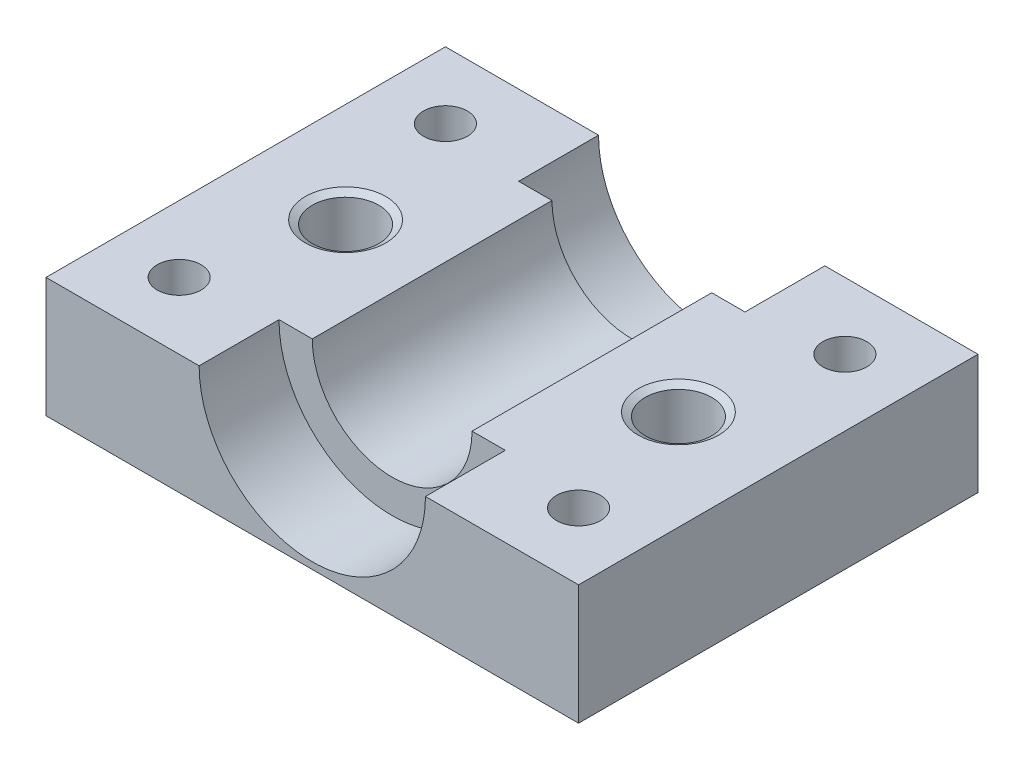
SolidWorks part; units mm, degrees
material "Д16Т ГОСТ 4784-74"
ref_plane "Спереди" through (0, 0, 0) normal (0, 0, 1) x (1, 0, 0)
ref_plane "Сверху" through (0, 0, 0) normal (0, 1, 0) x (1, 0, 0)
ref_plane "Справа" through (0, 0, 0) normal (1, 0, 0) x (0, 0, -1)
sketch "Эскиз1" plane through (0, 0, 0) normal (0, 0, 1) x (1, 0, 0)
  line L0 (28.5, 9) -> (40, 9)
  line L1 (0, 0) -> (40, 0)
  line L2 (0, 0) -> (0, 9)
  line L3 (0, 9) -> (11.5, 9)
  line L4 (40, 0) -> (40, 9)
  line L5 (11.5, 9) -> (28.5, 9) construction
  arc A0 (11.5, 9) -> (28.5, 9) centre (20, 9) ccw
  dimension "D1" = 17
  dimension "D2" = 9
  dimension "D3" = 40
extrude "Бобышка-Вытянуть1" add sketch "Эскиз1" along normal blind 24 and the other way blind 6
sketch "Эскиз3" plane through (0, 0, 0) normal (0, 0, 1) x (1, 0, 0)
  line L0 (11.5, 9) -> (14, 9)
  line L1 (26, 9) -> (28.5, 9)
  arc A0 (14, 9) -> (26, 9) centre (20, 9) ccw
  arc A1 (11.5, 9) -> (28.5, 9) centre (20, 9) ccw
  arc A2 (11.5, 9) -> (28.5, 9) centre (20, 9) ccw construction
  dimension "D1" = 12
extrude "Бобышка-Вытянуть2" add sketch "Эскиз3" along normal blind 18
hole_wizard "Отверстие обработанное метчиком M41" positions "Эскиз5" profile "Эскиз4" tap size "M4" standard "DIN"
sketch "Эскиз5" plane through (0, 0, 0) normal (0, -1, 0) x (1, 0, 0)
  line L0 (20, 24) -> (20, -6) construction
  line L1 (0, 24) -> (40, 24) construction
  line L2 (0, -6) -> (40, -6) construction
  line L4 (20, 9) -> (40, 9) construction
  line L5 (40, -6) -> (40, 24) construction
  point P0 (35, 19)
  point P18 (35, -1)
  point P19 (5, 19)
  point P20 (5, -1)
  dimension "D1" = 15
  dimension "D2" = 10
sketch "Эскиз4" plane through (35, 0, 19) normal (1, 0, 0) x (0, 0, -1)
  line L0 (0, 0) -> (0, 12.4914)
  line L1 (0, 12.4914) -> (1.65, 11.5)
  line L2 (1.65, 11.5) -> (1.65, 0.2165)
  line L3 (1.65, 0.2165) -> (2.025, 0)
  line L5 (2.025, 0) -> (0, 0)
  line L6 (-1.65, 0.2165) -> (-2.025, 0) construction
  line L10 (0, 12.4914) -> (-1.65, 11.5) construction
  line L11 (0, -6.35) -> (0, 107.95) construction
  dimension "Диаметр сверла" = 3.3
  dimension "Глубина сверла" = 11.5
  dimension "Диаметр передней зенковки" = 4.05
  dimension "Угол передней зенковки" = 120
  dimension "Угол заточки сверла" = 118
cosmetic thread "Отверстие резьбы1" parameters "D1"=8, "D2"=4
cosmetic thread "Отверстие резьбы2" parameters "D1"=8, "D2"=4
cosmetic thread "Отверстие резьбы3" parameters "D1"=8, "D2"=4
cosmetic thread "Отверстие резьбы4" parameters "D1"=8, "D2"=4
hole_wizard "Отверстие обработанное метчиком M61" positions "Эскиз7" profile "Эскиз6" tap size "M6" standard "DIN"
sketch "Эскиз7" plane through (0, 9, 0) normal (0, 1, 0) x (-1, 0, 0)
  line L0 (-32.5, -6) -> (-32.5, 24)
  line L1 (-40, -6) -> (-28.5, -6) construction
  line L2 (-40, 24) -> (-28.5, 24) construction
  line L4 (-20, 24) -> (-20, -6) construction
  line L5 (-11.5, 24) -> (-28.5, 24) construction
  line L6 (-28.5, -6) -> (-11.5, -6) construction
  point P0 (-32.5, 9)
  point P18 (-7.5, 9)
  dimension "D1" = 25
sketch "Эскиз6" plane through (32.5, 9, 9) normal (1, 0, 0) x (0, 0, 1)
  line L0 (0, 0) -> (0, 18.5022)
  line L1 (0, 18.5022) -> (2.5, 17)
  line L2 (2.5, 17) -> (2.5, 0.3031)
  line L3 (2.5, 0.3031) -> (3.025, 0)
  line L5 (3.025, 0) -> (0, 0)
  line L6 (-2.5, 0.3031) -> (-3.025, 0) construction
  line L10 (0, 18.5022) -> (-2.5, 17) construction
  line L11 (0, -6.35) -> (0, 107.95) construction
  dimension "Диаметр сверла" = 5
  dimension "Глубина сверла" = 17
  dimension "Диаметр передней зенковки" = 6.05
  dimension "Угол передней зенковки" = 120
  dimension "Угол заточки сверла" = 118
cosmetic thread "Отверстие резьбы5" parameters "D1"=12, "D2"=6
cosmetic thread "Отверстие резьбы6" parameters "D1"=12, "D2"=6
